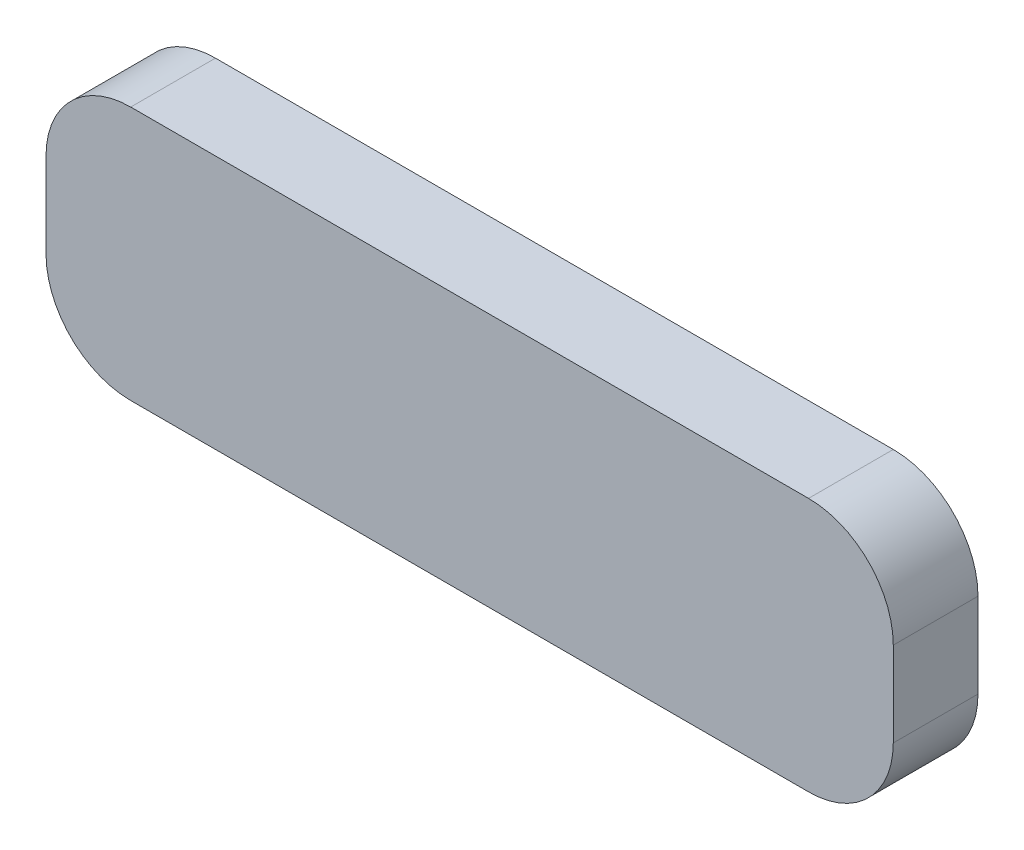
SolidWorks part; units mm, degrees
material "Nylon 101"
ref_plane "Front Plane" through (0, 0, 0) normal (0, 0, 1) x (1, 0, 0)
ref_plane "Top Plane" through (0, 0, 0) normal (0, 1, 0) x (1, 0, 0)
ref_plane "Right Plane" through (0, 0, 0) normal (1, 0, 0) x (0, 0, -1)
sketch "Sketch2" plane through (0, 0, 0) normal (0, 0, 1) x (1, 0, 0)
  line L1 (10, 0) -> (90, 0)
  line L2 (0, 10) -> (0, 20)
  line L3 (10, 30) -> (90, 30)
  line L4 (100, 10) -> (100, 20)
  arc A0 (0, 20) -> (10, 30) centre (10, 20) cw
  arc A1 (10, 0) -> (0, 10) centre (10, 10) cw
  arc A2 (90, 30) -> (100, 20) centre (90, 20) cw
  arc A3 (90, 0) -> (100, 10) centre (90, 10) ccw
  circle A4 centre (10, 15.4835) radius 2.4
  point P7 (0, 30)
  point P10 (0, 0)
  point P13 (100, 30)
  point P18 (0, 0)
  dimension "D3" = 10
  dimension "D4" = 10
  dimension "D5" = 10
  dimension "D6" = 10
  dimension "D7" = 4.8
  dimension "D1" = 100
  dimension "D2" = 30
extrude "Boss-Extrude1" add sketch "Sketch2" along normal blind 10 contours L3 A2 L4 A3 L1 A1 L2 A0
